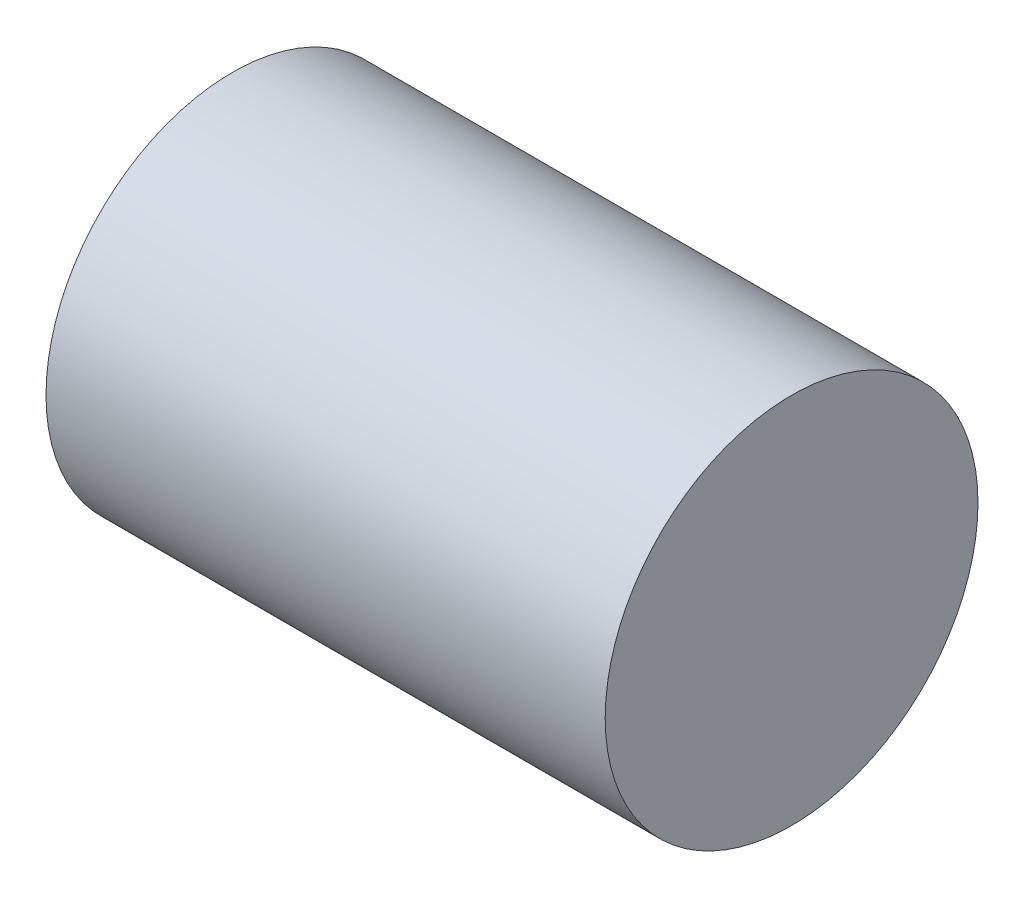
SolidWorks part; units mm, degrees
ref_plane "Front Plane" through (0, 0, 0) normal (0, 0, 1) x (1, 0, 0)
ref_plane "Top Plane" through (0, 0, 0) normal (0, 1, 0) x (1, 0, 0)
ref_plane "Right Plane" through (0, 0, 0) normal (1, 0, 0) x (0, 0, -1)
sketch "Sketch1" plane through (0, 0, 0) normal (1, 0, 0) x (0, 0, -1)
  circle A0 centre (0, 0) radius 12.7
  dimension "D1" = 25.4
extrude "Boss-Extrude1" add sketch "Sketch1" along normal blind 38.1
